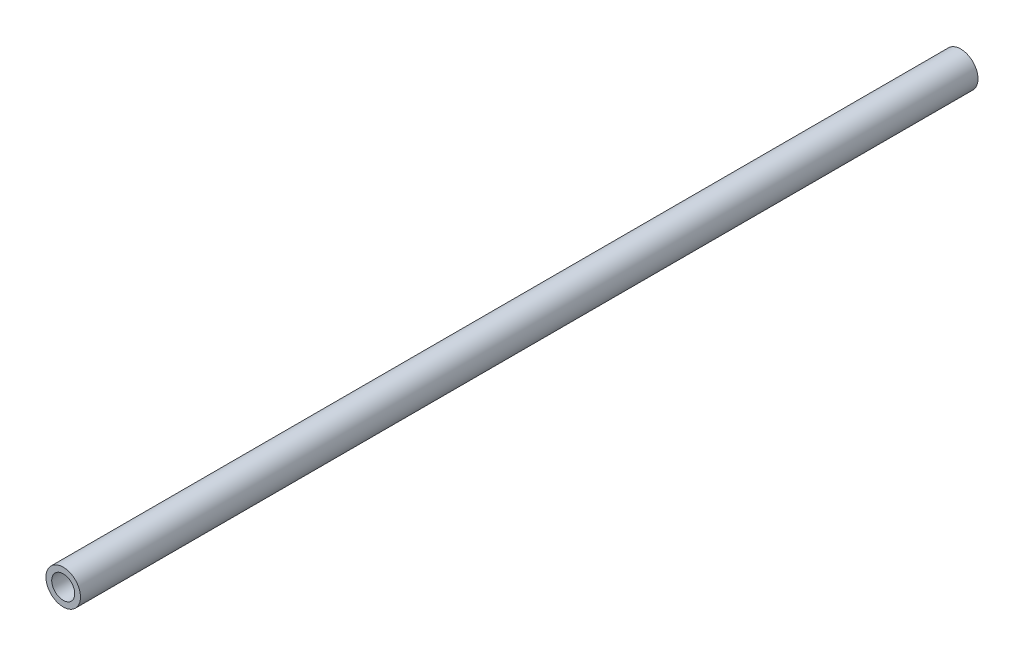
SolidWorks part; units mm, degrees
ref_plane "Front Plane" through (0, 0, 0) normal (0, 0, 1) x (1, 0, 0)
ref_plane "Top Plane" through (0, 0, 0) normal (0, 1, 0) x (1, 0, 0)
ref_plane "Right Plane" through (0, 0, 0) normal (1, 0, 0) x (0, 0, -1)
sketch "Sketch1" plane through (0, 0, 0) normal (0, 0, 1) x (1, 0, 0)
  circle A0 centre (0, 0) radius 3.175
  circle A1 centre (0, 0) radius 4.7625
  dimension "D1" = 6.35
  dimension "D2" = 9.525
extrude "Boss-Extrude1" add sketch "Sketch1" along normal mid plane 247.65
